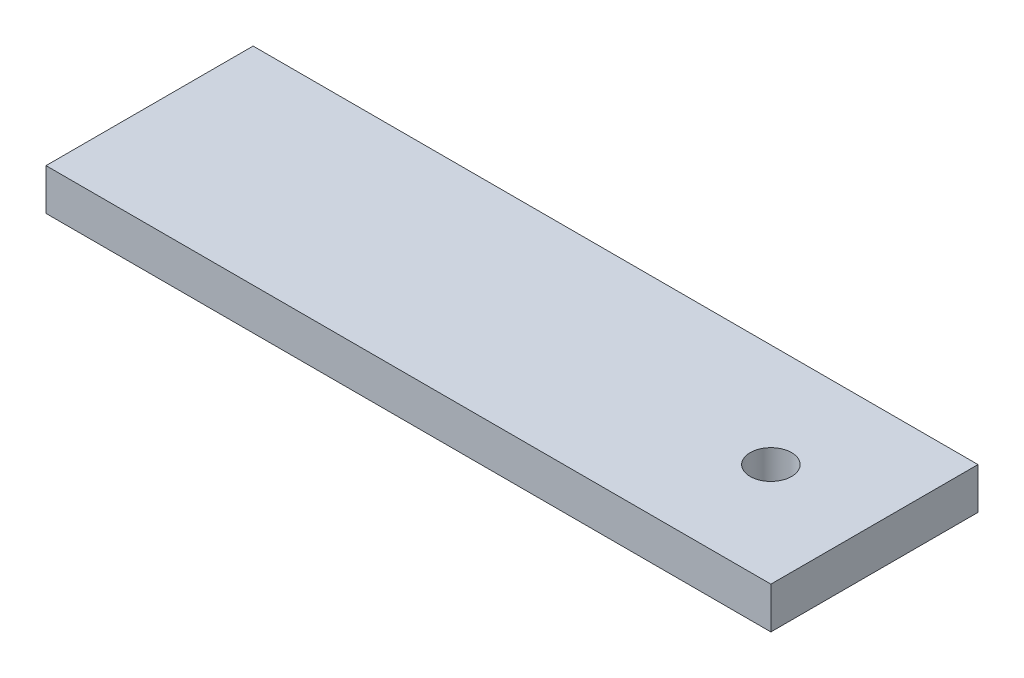
SolidWorks part; units mm, degrees
ref_plane "Front Plane" through (0, 0, 0) normal (0, 0, 1) x (1, 0, 0)
ref_plane "Top Plane" through (0, 0, 0) normal (0, 1, 0) x (1, 0, 0)
ref_plane "Right Plane" through (0, 0, 0) normal (1, 0, 0) x (0, 0, -1)
sketch "Sketch1" plane through (0, 0, 0) normal (0, 1, 0) x (1, 0, 0)
  line L1 (0, 0) -> (70, 0)
  line L2 (0, 0) -> (0, 20)
  line L3 (0, 20) -> (70, 20)
  line L4 (70, 0) -> (70, 20)
  dimension "D1" = 70
  dimension "D2" = 20
extrude "Boss-Extrude1" add sketch "Sketch1" along normal blind 4
sketch "Sketch2" plane through (0, 4, 0) normal (0, 1, 0) x (1, 0, 0)
  line L0 (70, 0) -> (70, 20) construction
  line L1 (0, 0) -> (70, 0) construction
  circle A0 centre (60, 10) radius 2
  dimension "D1" = 4
  dimension "D2" = 10
  dimension "D3" = 10
extrude "Cut-Extrude1" cut sketch "Sketch2" against normal blind 4
